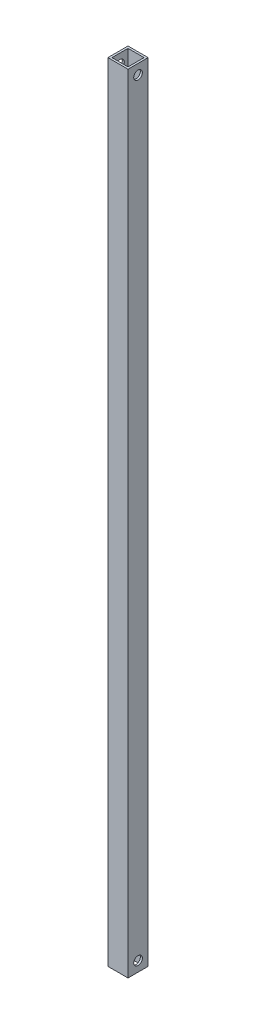
SolidWorks part; units mm, degrees
material "5052-H34"
ref_plane "正面" through (0, 0, 0) normal (0, 0, 1) x (1, 0, 0)
ref_plane "平面" through (0, 0, 0) normal (0, 1, 0) x (1, 0, 0)
ref_plane "右側面" through (0, 0, 0) normal (1, 0, 0) x (0, 0, -1)
sketch "ｽｹｯﾁ1" plane through (0, 0, 0) normal (0, 1, 0) x (1, 0, 0)
  line L1 (-5, 5) -> (5, 5)
  line L2 (-5, 5) -> (-5, -5)
  line L3 (-5, -5) -> (5, -5)
  line L4 (5, 5) -> (5, -5)
  line L5 (-5, 5) -> (5, -5) construction
  line L6 (-5, -5) -> (5, 5) construction
  point P0 (0, 0)
  dimension "D1" = 10
  dimension "D2" = 10
extrude "押し出し-薄板1" add sketch "ｽｹｯﾁ1" along normal blind 391.8377 thin
sketch "ｽｹｯﾁ2" plane through (5, 0, 0) normal (1, 0, 0) x (0, 0, -1)
  line L0 (-5, 195.9188) -> (5, 195.9188) construction
  line L1 (-5, 391.8377) -> (-5, 0) construction
  line L2 (5, 391.8377) -> (5, 0) construction
  line L3 (0, 0) -> (0, 5) construction
  circle A0 centre (0, 5) radius 2.15
  circle A1 centre (0, 386.8377) radius 2.15
  dimension "D2" = 4.3
  dimension "D1" = 5
extrude "ｶｯﾄ - 押し出し1" cut sketch "ｽｹｯﾁ2" against normal through all
equation "\"D1@押し出し-薄板1\"=10+sqr(270^2+270^2)"
